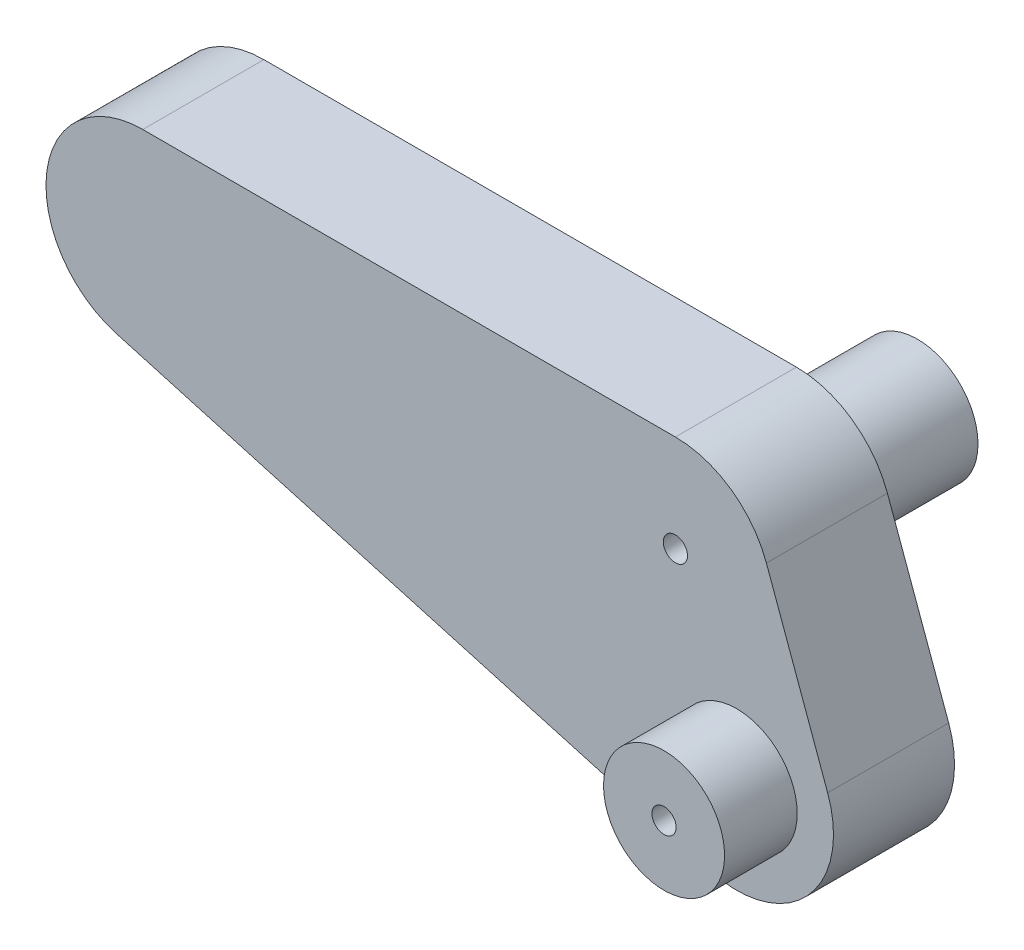
SolidWorks part; units mm, degrees
material "ABS"
ref_plane "Front Plane" through (0, 0, 0) normal (0, 0, 1) x (1, 0, 0)
ref_plane "Top Plane" through (0, 0, 0) normal (0, 1, 0) x (1, 0, 0)
ref_plane "Right Plane" through (0, 0, 0) normal (1, 0, 0) x (0, 0, -1)
sketch "Sketch1" plane through (0, 0, 0) normal (0, 0, 1) x (1, 0, 0)
  line L0 (0, 0) -> (-22, 0)
  line L1 (0, 0) -> (2.5309, -6.9537)
  dimension "D1" = 22
  dimension "D2" = 7.4
  dimension "D3" = 110
sketch "Sketch2" plane through (0, 0, 0) normal (0, 0, 1) x (1, 0, 0)
  line L0 (-22, 4) -> (0, 4)
  line L1 (3.7588, 1.3681) -> (6.2897, -5.5856)
  line L2 (1.4401, -10.8021) -> (-23.0909, -3.8484)
  circle A0 centre (-22, 0) radius 2.5
  arc A1 (-22, 4) -> (-23.0909, -3.8484) centre (-22, 0) ccw
  circle A2 centre (0, 0) radius 2.5
  arc A3 (3.7588, 1.3681) -> (0, 4) centre (0, 0) ccw
  circle A4 centre (2.5309, -6.9537) radius 2.5
  arc A5 (1.4401, -10.8021) -> (6.2897, -5.5856) centre (2.5309, -6.9537) ccw
  dimension "D1" = 5
  dimension "D2" = 8
  dimension "D3" = 5
  dimension "D4" = 8
  dimension "D5" = 5
  dimension "D6" = 8
extrude "Boss-Extrude1" add sketch "Sketch2" along normal blind 5
sketch "Sketch3" plane through (0, 0, 5) normal (0, 0, 1) x (1, 0, 0)
  circle A0 centre (0, 0) radius 2.5
  circle A1 centre (0, 0) radius 0.5
  dimension "D1" = 5
  dimension "D2" = 1
extrude "Boss-Extrude2" add sketch "Sketch3" against normal blind 10
sketch "Sketch4" plane through (0, 0, 0) normal (0, 0, -1) x (-1, 0, 0)
  circle A0 centre (-2.5309, -6.9537) radius 2.5
  circle A1 centre (-2.5309, -6.9537) radius 0.5
  dimension "D1" = 1
  dimension "D2" = 5
extrude "Boss-Extrude3" add sketch "Sketch4" against normal blind 8
sketch "Sketch5" plane through (0, 0, 0) normal (0, 0, -1) x (-1, 0, 0)
  circle A0 centre (22, 0) radius 2.5
  dimension "D1" = 5
extrude "Boss-Extrude4" add sketch "Sketch5" against normal blind 5
